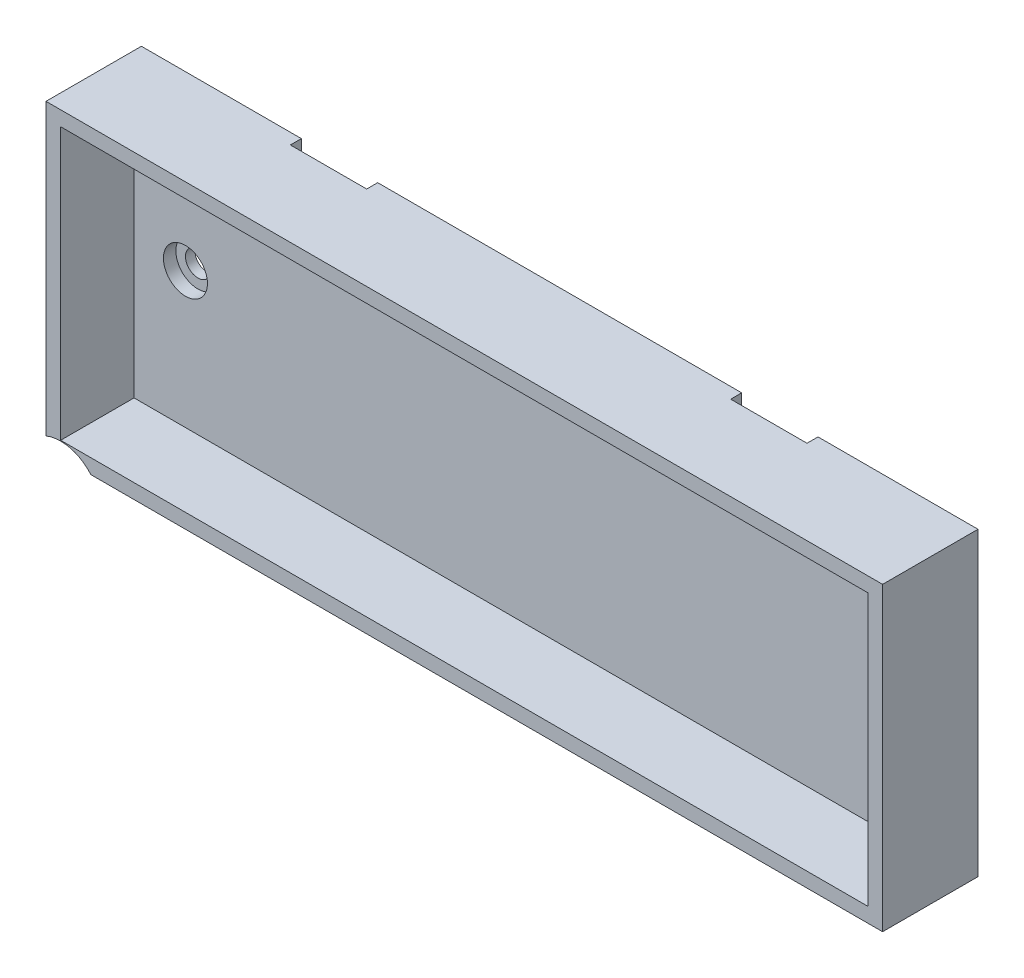
SolidWorks part; units mm, degrees
other "Battery Tray Right"
ref_plane "Front Plane" through (0, 0, 0) normal (0, 0, 1) x (1, 0, 0)
ref_plane "Top Plane" through (0, 0, 0) normal (0, 1, 0) x (1, 0, 0)
ref_plane "Right Plane" through (0, 0, 0) normal (1, 0, 0) x (0, 0, -1)
sketch3d "Main Profile Sketch datum points"
  point P0 (0, 0, 61.5)
  point P1 (10, 0, 61.5)
  point P2 (0, 10, 61.5)
ref_plane "Main Profile Sketch plane" through (0, 0, 61.5) normal (0, 0, 1) x (1, 0, 0)
sketch "Main Profile Sketch" plane through (0, 0, 61.5) normal (0, 0, 1) x (1, 0, 0)
  line L0 (-272, -6) -> (-158, -6)
  line L1 (-158, -6) -> (-158, -47)
  line L2 (-265.8878, -47) -> (-158, -47)
  line L3 (-272, -6) -> (-272, -45.484)
  line L4 (-270, -8) -> (-270, -45)
  line L5 (-270, -45) -> (-160, -45)
  line L6 (-160, -8) -> (-160, -45)
  line L7 (-270, -8) -> (-160, -8)
  arc A0 (-265.8878, -47) -> (-272, -45.484) centre (-270, -50.5) ccw
extrude "Main Extrusion" add sketch "Main Profile Sketch" against normal blind 10 separate body
sketch3d "Detail Profile 2 Sketch datum points"
  point P0 (0, 0, 51.5)
  point P1 (10, 0, 51.5)
  point P2 (0, 10, 51.5)
ref_plane "Detail Profile 2 Sketch plane" through (0, 0, 51.5) normal (0, 0, 1) x (1, 0, 0)
sketch "Detail Profile 2 Sketch" plane through (0, 0, 51.5) normal (0, 0, 1) x (1, 0, 0)
  line L0 (-272, -6) -> (-158, -6)
  line L1 (-158, -6) -> (-158, -47)
  line L2 (-265.8878, -47) -> (-158, -47)
  line L3 (-272, -6) -> (-272, -45.484)
  arc A0 (-265.8878, -47) -> (-272, -45.484) centre (-270, -50.5) ccw
  circle A1 centre (-263, -26.5) radius 3
  circle A2 centre (-167, -26.5) radius 3
extrude "Detail Extrusion 2" add sketch "Detail Profile 2 Sketch" against normal blind 1.5
sketch3d "Detail Profile 3 Sketch datum points"
  point P0 (0, 0, 50)
  point P1 (10, 0, 50)
  point P2 (0, 10, 50)
ref_plane "Detail Profile 3 Sketch plane" through (0, 0, 50) normal (0, 0, 1) x (1, 0, 0)
sketch "Detail Profile 3 Sketch" plane through (0, 0, 50) normal (0, 0, 1) x (1, 0, 0)
  line L0 (-272, -6) -> (-250.2, -6)
  line L1 (-250.2, -6) -> (-250.2, -47)
  line L2 (-265.8878, -47) -> (-250.2, -47)
  line L3 (-272, -6) -> (-272, -45.484)
  line L4 (-179.8, -6) -> (-158, -6)
  line L5 (-158, -6) -> (-158, -47)
  line L6 (-179.8, -47) -> (-158, -47)
  line L7 (-179.8, -6) -> (-179.8, -47)
  line L8 (-239.8, -6) -> (-190.2, -6)
  line L9 (-190.2, -6) -> (-190.2, -47)
  line L10 (-239.8, -47) -> (-190.2, -47)
  line L11 (-239.8, -6) -> (-239.8, -47)
  arc A0 (-265.8878, -47) -> (-272, -45.484) centre (-270, -50.5) ccw
  circle A1 centre (-263, -26.5) radius 3
  circle A2 centre (-167, -26.5) radius 3
extrude "Detail Extrusion 3" add sketch "Detail Profile 3 Sketch" against normal blind 0.2
sketch3d "Detail Profile 4 Sketch datum points"
  point P0 (0, 0, 49.8)
  point P1 (10, 0, 49.8)
  point P2 (0, 10, 49.8)
ref_plane "Detail Profile 4 Sketch plane" through (0, 0, 49.8) normal (0, 0, 1) x (1, 0, 0)
sketch "Detail Profile 4 Sketch" plane through (0, 0, 49.8) normal (0, 0, 1) x (1, 0, 0)
  line L0 (-272, -6) -> (-250.2, -6)
  line L1 (-250.2, -6) -> (-250.2, -47)
  line L2 (-265.8878, -47) -> (-250.2, -47)
  line L3 (-272, -6) -> (-272, -45.484)
  line L4 (-239.8, -6) -> (-190.2, -6)
  line L5 (-190.2, -6) -> (-190.2, -47)
  line L6 (-239.8, -47) -> (-190.2, -47)
  line L7 (-239.8, -6) -> (-239.8, -47)
  line L8 (-179.8, -6) -> (-158, -6)
  line L9 (-158, -6) -> (-158, -47)
  line L10 (-179.8, -47) -> (-158, -47)
  line L11 (-179.8, -6) -> (-179.8, -47)
  arc A0 (-265.8878, -47) -> (-272, -45.484) centre (-270, -50.5) ccw
  circle A1 centre (-263, -26.5) radius 1.7
  circle A2 centre (-167, -26.5) radius 1.7
extrude "Detail Extrusion 4" add sketch "Detail Profile 4 Sketch" against normal blind 1.3
